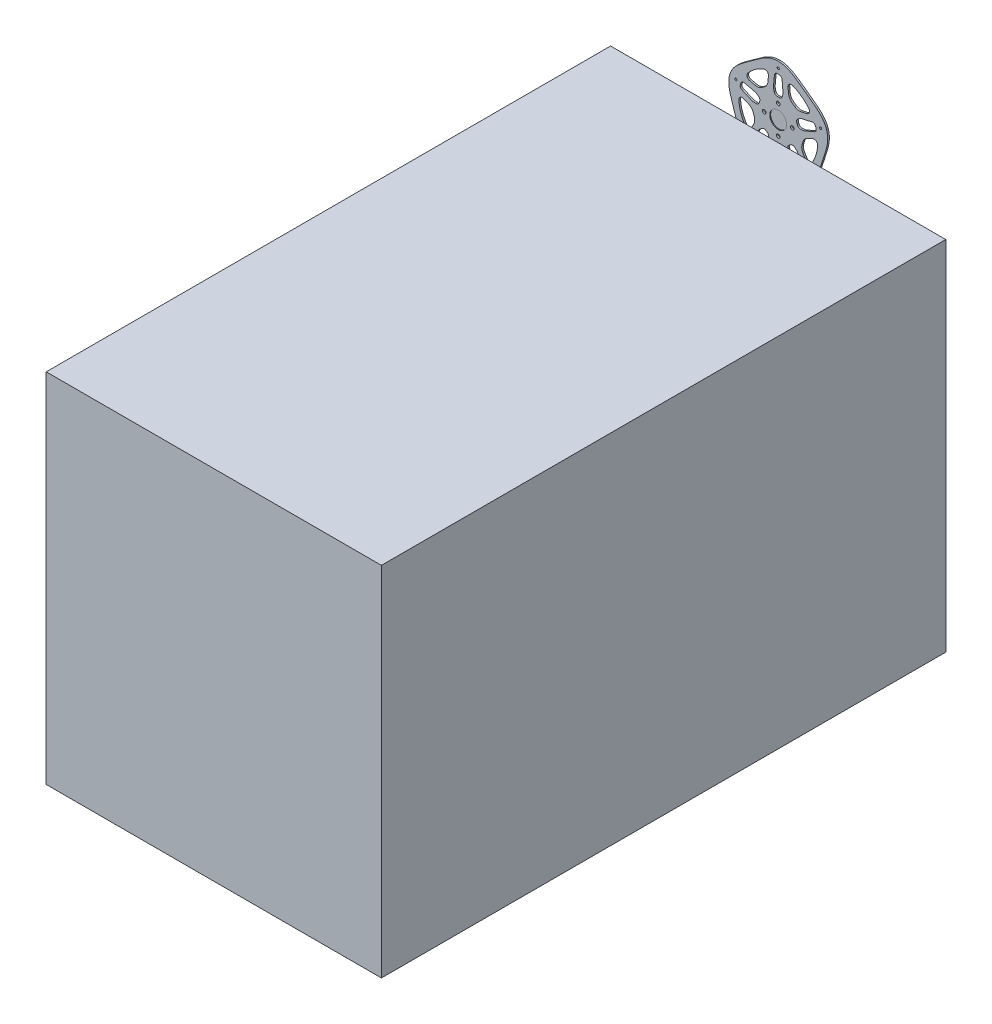
SolidWorks part; units mm, degrees
material "Stop 1060"
ref_plane "Płaszczyzna przednia" through (0, 0, 0) normal (0, 0, 1) x (1, 0, 0)
ref_plane "Płaszczyzna górna" through (0, 0, 0) normal (0, 1, 0) x (1, 0, 0)
ref_plane "Płaszczyzna prawa" through (0, 0, 0) normal (1, 0, 0) x (0, 0, -1)
sketch "Szkic1" plane through (0, 0, 0) normal (0, 0, 1) x (1, 0, 0)
  line L0 (0, 0) -> (51.1373, 70.3845) construction
  line L1 (0, 0) -> (0, 87) construction
  line L42 (64.6668, 37.9895) -> (41.3071, 32.5965)
  line L43 (69.2558, 28.7859) -> (41.6924, 22.4224)
  line L44 (38.6664, 21.1739) -> (30.949, 16.3814)
  line L45 (35.8646, 30.1162) -> (26.2605, 23.1384)
  line L46 (43.7274, 5.5975) -> (34.667, 4.9385)
  line L47 (72.9491, 17.4193) -> (46.9094, 6.3661)
  line L48 (-6.7939, 65.4105) -> (-8.4413, 46.5807)
  line L49 (-8.189, 43.317) -> (-7.2584, 39.5397)
  line L50 (69.805, 5.2211) -> (52.5779, -2.0914)
  line L51 (46.7169, -3.2838) -> (34.8456, -3.2838)
  line L52 (56.1133, -49.7624) -> (43.7657, -29.2126)
  line L53 (-7.4667, 69.6006) -> (-7.4667, 29.102) construction
  line L54 (48.7783, -56.9709) -> (34.2086, -32.7229)
  line L55 (32.0861, -30.2308) -> (25.1434, -24.3721)
  line L56 (39.725, -24.8029) -> (30.1209, -17.8251)
  line L57 (-17.3877, 59.0596) -> (-18.2365, 49.3583)
  line L58 (18.836, -39.8576) -> (15.4095, -31.4442)
  line L59 (39.1092, -63.9958) -> (20.5503, -42.6462)
  line L60 (26.5365, -64.7751) -> (14.2585, -50.6508)
  line L61 (-17.5594, 43.4157) -> (-13.891, 32.1254)
  line L62 (11.3132, -45.4452) -> (7.6448, -34.1549)
  line L63 (-29.9869, -68.7443) -> (-14.2585, -50.6508)
  line L64 (-39.1092, -63.9958) -> (-20.5503, -42.6462)
  line L65 (-18.836, -39.8576) -> (-15.4095, -31.4442)
  line L66 (-11.3132, -45.4452) -> (-7.6448, -34.1549)
  line L67 (-32.0861, -30.2308) -> (-25.1434, -24.3721)
  line L68 (-48.7783, -56.9709) -> (-34.2086, -32.7229)
  line L69 (-53.4046, -45.2543) -> (-43.7657, -29.2126)
  line L70 (-39.725, -24.8029) -> (-30.1209, -17.8251)
  line L71 (-74.6462, 7.2761) -> (-52.5779, -2.0914)
  line L72 (-72.9491, 17.4193) -> (-46.9094, 6.3661)
  line L73 (-43.7274, 5.5975) -> (-34.667, 4.9385)
  line L74 (0, 0) -> (32.9395, 101.3773) construction
  line L111 (-46.7169, -3.2838) -> (-34.8456, -3.2838)
  line L112 (-38.6664, 21.1739) -> (-30.949, 16.3814)
  line L113 (-69.2558, 28.7859) -> (-41.6924, 22.4224)
  line L114 (-59.5423, 36.8064) -> (-41.3071, 32.5965)
  line L115 (-35.8646, 30.1162) -> (-26.2605, 23.1384)
  line L116 (-29.0561, 35.0629) -> (-24.3679, 38.469)
  line L117 (24.3679, 38.469) -> (29.0561, 35.0629)
  line L118 (44.1163, -11.2877) -> (42.3256, -16.799)
  line L119 (2.8975, -45.4452) -> (-2.8975, -45.4452)
  line L120 (17.5594, 43.4157) -> (13.891, 32.1254)
  line L121 (8.189, 43.317) -> (7.2584, 39.5397)
  line L122 (16.6054, 68.0019) -> (18.2365, 49.3583)
  line L123 (5.9758, 74.7616) -> (8.4413, 46.5807)
  line L124 (-42.3256, -16.799) -> (-44.1163, -11.2877)
  circle A0 centre (0, 0) radius 79 construction
  circle A2 centre (0, 0) radius 25 construction
  circle A3 centre (0, 0) radius 3.3
  circle A4 centre (0, 25) radius 3.2
  circle A5 centre (0, 79) radius 1.9
  circle A6 centre (25, 0) radius 3.2
  circle A7 centre (0, -25) radius 3.2
  circle A8 centre (-25, 0) radius 3.2
  circle A9 centre (75.1335, 24.4123) radius 1.9
  circle A10 centre (46.435, -63.9123) radius 1.9
  circle A11 centre (-46.435, -63.9123) radius 1.9
  circle A12 centre (-75.1335, 24.4123) radius 1.9
  circle A13 centre (0, 0) radius 87 construction
  arc A54 (35.8646, 30.1162) -> (41.3071, 32.5965) centre (44.6814, 17.9809) cw
  arc A55 (38.6664, 21.1739) -> (41.6924, 22.4224) centre (43.9419, 12.6787) cw
  arc A56 (43.7274, 5.5975) -> (46.9094, 6.3661) centre (43.0021, 15.5711) ccw
  arc A57 (46.7169, -3.2838) -> (52.5779, -2.0914) centre (46.7169, 11.7162) ccw
  arc A58 (39.725, -24.8029) -> (43.7657, -29.2126) centre (30.9082, -36.9381) cw
  arc A59 (32.0861, -30.2308) -> (34.2086, -32.7229) centre (25.6369, -37.8733) cw
  circle A60 centre (0, 0) radius 70
  arc A61 (-8.189, 43.317) -> (-8.4413, 46.5807) centre (1.5207, 45.7091) cw
  arc A62 (18.836, -39.8576) -> (20.5503, -42.6462) centre (28.0974, -36.0857) ccw
  arc A63 (11.3132, -45.4452) -> (14.2585, -50.6508) centre (25.5791, -40.8099) ccw
  arc A64 (-11.3132, -45.4452) -> (-14.2585, -50.6508) centre (-25.5791, -40.8099) cw
  arc A65 (-18.2391, 49.3276) -> (-18.2365, 49.3583) centre (-3.2936, 48.051) cw
  arc A66 (-18.836, -39.8576) -> (-20.5503, -42.6462) centre (-28.0974, -36.0857) cw
  arc A67 (-32.0861, -30.2308) -> (-34.2086, -32.7229) centre (-25.6369, -37.8733) ccw
  arc A68 (-39.725, -24.8029) -> (-43.7657, -29.2126) centre (-30.9082, -36.9381) ccw
  arc A69 (8.189, 43.317) -> (8.4413, 46.5807) centre (-1.5207, 45.7091) ccw
  arc A70 (-46.7169, -3.2838) -> (-52.5779, -2.0914) centre (-46.7169, 11.7162) cw
  arc A71 (-43.7274, 5.5975) -> (-46.9094, 6.3661) centre (-43.0021, 15.5711) cw
  arc A72 (-38.6664, 21.1739) -> (-41.6924, 22.4224) centre (-43.9419, 12.6787) ccw
  arc A73 (17.5594, 43.4157) -> (18.2365, 49.3583) centre (3.2936, 48.051) ccw
  arc A74 (-41.2772, 32.5895) -> (-41.3071, 32.5965) centre (-44.6814, 17.9809) ccw
  arc A75 (-24.3679, 38.469) -> (-18.2391, 49.3276) centre (-33.1847, 50.6043) ccw
  arc A76 (-41.2772, 32.5895) -> (-29.0561, 35.0629) centre (-37.8729, 47.1981) ccw
  arc A77 (29.0561, 35.0629) -> (41.2772, 32.5895) centre (37.8729, 47.1981) ccw
  arc A78 (18.2391, 49.3276) -> (24.3679, 38.469) centre (33.1847, 50.6043) ccw
  arc A79 (42.3256, -16.799) -> (43.7498, -29.1862) centre (56.5914, -21.4342) ccw
  arc A80 (52.5496, -2.1034) -> (44.1163, -11.2877) centre (58.3822, -15.9229) ccw
  arc A81 (-2.8975, -45.4452) -> (-14.2383, -50.6276) centre (-2.8975, -60.4452) ccw
  arc A82 (14.2383, -50.6276) -> (2.8975, -45.4452) centre (2.8975, -60.4452) ccw
  arc A83 (-44.1163, -11.2877) -> (-52.5496, -2.1034) centre (-58.3822, -15.9229) ccw
  arc A84 (-43.7498, -29.1862) -> (-42.3256, -16.799) centre (-56.5914, -21.4342) ccw
  arc A85 (-7.4667, 69.6006) -> (0, 70) centre (0, 0) ccw
  arc A86 (-1.9524, 69.9728) -> (0, 70) centre (0, 0) cw
  arc A87 (-6.7939, 65.4105) -> (-1.9524, 69.9728) centre (-1.8129, 64.9747) cw
  arc A88 (-25.5554, 65.1684) -> (-59.5423, 36.8064) centre (0, 0) ccw
  arc A89 (-17.3877, 59.0596) -> (-25.5554, 65.1684) centre (-23.3649, 59.5826) ccw
  circle A90 centre (0, 0) radius 35
  arc A91 (17.3877, 59.0596) -> (25.5554, 65.1684) centre (23.3649, 59.5826) cw
  arc A92 (6.7939, 65.4105) -> (1.9524, 69.9728) centre (1.8129, 64.9747) ccw
  arc A93 (61.5421, 1.7137) -> (69.8759, -4.1664) centre (63.8865, -3.8093) cw
  arc A94 (64.3085, 13.7516) -> (67.1514, 19.766) centre (62.3548, 18.3541) ccw
  arc A95 (60.1096, 26.6743) -> (65.9447, 23.4796) centre (61.2344, 21.8025) cw
  arc A96 (50.7959, 34.7871) -> (54.0818, 44.4427) centre (49.4462, 40.6334) ccw
  arc A97 (20.6474, -58.0005) -> (17.6303, -67.7434) centre (16.1192, -61.9368) cw
  arc A98 (32.9509, -56.9116) -> (39.5495, -57.7567) centre (36.7245, -53.6313) ccw
  arc A99 (43.9437, -48.9248) -> (42.7085, -55.4616) centre (39.6579, -51.5) cw
  arc A100 (48.7813, -37.56) -> (58.9798, -37.7013) centre (53.9243, -34.4698) ccw
  arc A101 (-48.7813, -37.56) -> (-58.9798, -37.7013) centre (-53.9243, -34.4698) cw
  arc A102 (-43.9437, -48.9248) -> (-42.7085, -55.4616) centre (-39.6579, -51.5) ccw
  arc A103 (-32.9509, -56.9116) -> (-39.5495, -57.7567) centre (-36.7245, -53.6313) cw
  arc A104 (-20.6474, -58.0005) -> (-17.6303, -67.7434) centre (-16.1192, -61.9368) ccw
  arc A105 (-50.7959, 34.7871) -> (-54.0818, 44.4427) centre (-49.4462, 40.6334) cw
  arc A106 (-60.1096, 26.6743) -> (-65.9447, 23.4796) centre (-61.2344, 21.8025) ccw
  arc A107 (-64.3085, 13.7516) -> (-67.1514, 19.766) centre (-62.3548, 18.3541) cw
  arc A108 (-61.5421, 1.7137) -> (-69.8759, -4.1664) centre (-63.8865, -3.8093) ccw
  arc A109 (-7.4667, 29.102) -> (6.8673, 29.2492) centre (0, 0) ccw
  arc A110 (-1.2229, 34.9786) -> (1.2229, 34.9786) centre (0, 0) cw
  arc A111 (-7.2584, 39.5397) -> (-1.2229, 34.9786) centre (-1.4326, 40.975) ccw
  arc A112 (7.2584, 39.5397) -> (1.2229, 34.9786) centre (1.4326, 40.975) cw
  arc A113 (35.3615, 19.1216) -> (32.8887, 11.9721) centre (38.5268, 14.0244) ccw
  arc A114 (39.8474, 5.3153) -> (33.6446, 9.6459) centre (39.4122, 11.2995) cw
  arc A115 (29.113, -27.7219) -> (21.5493, -27.5795) centre (25.2435, -32.3074) ccw
  arc A116 (17.3687, -36.2546) -> (19.5705, -29.0171) centre (22.9255, -33.9915) cw
  arc A117 (-17.3687, -36.2546) -> (-19.5705, -29.0171) centre (-22.9255, -33.9915) ccw
  arc A118 (-29.113, -27.7219) -> (-21.5493, -27.5795) centre (-25.2435, -32.3074) cw
  arc A119 (-39.8474, 5.3153) -> (-33.6446, 9.6459) centre (-39.4122, 11.2995) ccw
  arc A120 (-35.3615, 19.1216) -> (-32.8887, 11.9721) centre (-38.5268, 14.0244) cw
  spline S0 degree 3 poles (0, 87) (18.2248, 86.9986) (32.2889, 73.5369) (46.435, 63.9123) knots 0 0 0 0 1 1 1 1 construction
  spline S1 degree 3 poles (82.7419, 26.8845) (77.1088, 44.2169) (59.9599, 53.4327) (46.435, 63.9123) knots 0 0 0 0 1 1 1 1 construction
  spline S2 degree 3 poles (82.7419, 26.8845) (88.3724, 9.5512) (79.9156, -7.9844) (75.1335, -24.4123) knots 0 0 0 0 1 1 1 1 construction
  spline S3 degree 3 poles (51.1373, -70.3845) (65.8807, -59.6711) (69.3462, -40.5137) (75.1335, -24.4123) knots 0 0 0 0 1 1 1 1 construction
  spline S4 degree 3 poles (51.1373, -70.3845) (36.3923, -81.0957) (17.1016, -78.4715) (0, -79) knots 0 0 0 0 1 1 1 1 construction
  spline S5 degree 3 poles (-51.1373, -70.3845) (-36.3923, -81.0957) (-17.1016, -78.4715) (0, -79) knots 0 0 0 0 1 1 1 1 construction
  spline S6 degree 3 poles (-51.1373, -70.3845) (-65.8807, -59.6711) (-69.3462, -40.5137) (-75.1335, -24.4123) knots 0 0 0 0 1 1 1 1 construction
  spline S7 degree 3 poles (-82.7419, 26.8845) (-88.3724, 9.5512) (-79.9156, -7.9844) (-75.1335, -24.4123) knots 0 0 0 0 1 1 1 1 construction
  spline S8 degree 3 poles (-82.7419, 26.8845) (-77.1088, 44.2169) (-59.9599, 53.4327) (-46.435, 63.9123) knots 0 0 0 0 1 1 1 1 construction
  spline S9 degree 3 poles (0, 87) (-18.2248, 86.9986) (-32.2889, 73.5369) (-46.435, 63.9123) knots 0 0 0 0 1 1 1 1 construction
  spline S10 degree 1 poles (0, 90) (48.1992, 66.3406) knots 0 0 1 1 construction
  spline S11 degree 1 poles (85.5951, 27.8115) (48.1992, 66.3406) knots 0 0 1 1 construction
  spline S12 degree 1 poles (85.5951, 27.8115) (77.988, -25.3398) knots 0 0 1 1 construction
  spline S13 degree 1 poles (52.9007, -72.8115) (77.988, -25.3398) knots 0 0 1 1 construction
  spline S14 degree 1 poles (52.9007, -72.8115) (0, -82.0014) knots 0 0 1 1 construction
  spline S15 degree 1 poles (-52.9007, -72.8115) (0, -82.0014) knots 0 0 1 1 construction
  spline S16 degree 1 poles (-52.9007, -72.8115) (-77.988, -25.3398) knots 0 0 1 1 construction
  spline S17 degree 1 poles (-85.5951, 27.8115) (-77.988, -25.3398) knots 0 0 1 1 construction
  spline S18 degree 1 poles (-85.5951, 27.8115) (-48.1992, 66.3406) knots 0 0 1 1 construction
  spline S19 degree 1 poles (0, 90) (-48.1992, 66.3406) knots 0 0 1 1 construction
  spline S20 degree 3 poles (0, 90) (1.2173, 89.9999) (3.6733, 89.8856) (8.3842, 89.2383) (14.0239, 87.7208) (20.3782, 85.0183) (26.3875, 81.6762) (32.115, 77.9195) (37.6265, 73.9608) (42.0815, 70.6707) (45.5966, 68.1385) (47.3232, 66.9366) (48.1992, 66.3406) knots -0.000004 -0.000004 -0.000004 -0.000004 0.062609 0.125222 0.250448 0.375675 0.500901 0.626127 0.751353 0.87658 0.939193 1.001806 1.001806 1.001806 1.001806
  spline S21 degree 3 poles (48.1992, 66.3406) (49.0368, 65.6916) (50.7135, 64.4209) (54.2079, 61.8604) (58.7136, 58.6401) (64.1818, 54.6216) (69.5245, 50.3354) (74.56, 45.6529) (79.0938, 40.4447) (82.2798, 35.55) (84.3511, 31.2697) (85.2188, 28.9693) (85.5951, 27.8115) knots -0.000004 -0.000004 -0.000004 -0.000004 0.062609 0.125222 0.250448 0.375675 0.500901 0.626127 0.751353 0.87658 0.939193 1.001806 1.001806 1.001806 1.001806
  spline S22 degree 3 poles (85.5951, 27.8115) (85.9712, 26.6537) (86.6214, 24.2826) (87.4616, 19.6023) (87.761, 13.7697) (87.1544, 6.8913) (85.8329, 0.1433) (84.03, -6.4647) (81.9681, -12.9298) (80.2157, -18.1835) (78.8937, -22.3089) (78.2841, -24.3225) (77.988, -25.3398) knots -0.000004 -0.000004 -0.000004 -0.000004 0.062609 0.125222 0.250448 0.375675 0.500901 0.626127 0.751353 0.87658 0.939193 1.001806 1.001806 1.001806 1.001806
  spline S23 degree 3 poles (77.988, -25.3398) (77.6296, -26.337) (76.9392, -28.3242) (75.5838, -32.4389) (73.9136, -37.7192) (71.7815, -44.1615) (69.356, -50.5673) (66.4588, -56.8033) (62.9065, -62.7246) (59.236, -67.2672) (55.8052, -70.5598) (53.8855, -72.0959) (52.9007, -72.8115) knots -0.000004 -0.000004 -0.000004 -0.000004 0.062609 0.125222 0.250448 0.375675 0.500901 0.626127 0.751353 0.87658 0.939193 1.001806 1.001806 1.001806 1.001806
  spline S24 degree 3 poles (52.9007, -72.8115) (51.9158, -73.527) (49.8616, -74.8781) (45.67, -77.1235) (40.2154, -79.2106) (33.4862, -80.7592) (26.6601, -81.5876) (19.8184, -81.9149) (13.0325, -81.9518) (7.4945, -81.9087) (3.1624, -81.9262) (1.0591, -81.9687) (0, -82.0014) knots -0.000004 -0.000004 -0.000004 -0.000004 0.062609 0.125222 0.250448 0.375675 0.500901 0.626127 0.751353 0.87658 0.939193 1.001806 1.001806 1.001806 1.001806
  spline S25 degree 3 poles (0, -82.0014) (-1.0591, -81.9687) (-3.1624, -81.9262) (-7.4945, -81.9087) (-13.0325, -81.9518) (-19.8184, -81.9149) (-26.6601, -81.5876) (-33.4862, -80.7592) (-40.2154, -79.2106) (-45.67, -77.1235) (-49.8616, -74.8781) (-51.9158, -73.527) (-52.9007, -72.8115) knots -0.000004 -0.000004 -0.000004 -0.000004 0.062609 0.125222 0.250448 0.375675 0.500901 0.626127 0.751353 0.87658 0.939193 1.001806 1.001806 1.001806 1.001806
  spline S26 degree 3 poles (-52.9007, -72.8115) (-53.8855, -72.0959) (-55.8052, -70.5598) (-59.236, -67.2672) (-62.9065, -62.7246) (-66.4588, -56.8033) (-69.356, -50.5673) (-71.7815, -44.1615) (-73.9136, -37.7192) (-75.5838, -32.4389) (-76.9392, -28.3242) (-77.6296, -26.337) (-77.988, -25.3398) knots -0.000004 -0.000004 -0.000004 -0.000004 0.062609 0.125222 0.250448 0.375675 0.500901 0.626127 0.751353 0.87658 0.939193 1.001806 1.001806 1.001806 1.001806
  spline S27 degree 3 poles (-77.988, -25.3398) (-78.2841, -24.3225) (-78.8937, -22.3089) (-80.2157, -18.1835) (-81.9681, -12.9298) (-84.03, -6.4647) (-85.8329, 0.1433) (-87.1544, 6.8913) (-87.761, 13.7697) (-87.4616, 19.6023) (-86.6214, 24.2826) (-85.9712, 26.6537) (-85.5951, 27.8115) knots -0.000004 -0.000004 -0.000004 -0.000004 0.062609 0.125222 0.250448 0.375675 0.500901 0.626127 0.751353 0.87658 0.939193 1.001806 1.001806 1.001806 1.001806
  spline S28 degree 3 poles (-85.5951, 27.8115) (-85.2188, 28.9693) (-84.3511, 31.2697) (-82.2798, 35.55) (-79.0938, 40.4447) (-74.56, 45.6529) (-69.5245, 50.3354) (-64.1818, 54.6216) (-58.7136, 58.6401) (-54.2079, 61.8604) (-50.7135, 64.4209) (-49.0368, 65.6916) (-48.1992, 66.3406) knots -0.000004 -0.000004 -0.000004 -0.000004 0.062609 0.125222 0.250448 0.375675 0.500901 0.626127 0.751353 0.87658 0.939193 1.001806 1.001806 1.001806 1.001806
  spline S29 degree 3 poles (-48.1992, 66.3406) (-47.3232, 66.9366) (-45.5966, 68.1385) (-42.0815, 70.6707) (-37.6265, 73.9608) (-32.115, 77.9195) (-26.3875, 81.6762) (-20.3782, 85.0183) (-14.0239, 87.7208) (-8.3842, 89.2383) (-3.6733, 89.8856) (-1.2173, 89.9999) (0, 90) knots -0.000004 -0.000004 -0.000004 -0.000004 0.062609 0.125222 0.250448 0.375675 0.500901 0.626127 0.751353 0.87658 0.939193 1.001806 1.001806 1.001806 1.001806
  point P18 (0, 0)
  point P27 (0, 0)
  point P64 (0, 0)
  point P72 (-8.5859, 44.9279)
  point P166 (0, 0)
  point P188 (0.227, 0)
  point P198 (0, 0)
  point P260 (0, 0)
  point P291 (0, 0)
  point P369 (0.5409, 0.0601)
  dimension "D1" = 158
  dimension "D2" = 6.6
  dimension "D3" = 50
  dimension "D4" = 3.8
  dimension "D5" = 6.4
  dimension "D8" = 174
  dimension "D13" = 5
  dimension "D14" = 6
  dimension "D15" = 10
  dimension "D10" = 70
  dimension "D11" = 140
  dimension "D16" = 10
  dimension "D18" = 15
  dimension "D23" = 15
  dimension "D26" = 6
  dimension "D27" = 6
  dimension "D29" = 70
  dimension "D9" = 36
  dimension "D12" = 5
  dimension "D17" = 18
  dimension "D20" = 5
  dimension "D21" = 11.8713
  dimension "D22" = 18
  dimension "D19" = 3
  dimension "D6" = 4
  dimension "D7" = 5
  dimension "D24" = 5
  dimension "D25" = 5
  dimension "D28" = 5
extrude "Dodanie-wyciągnięcie1" add sketch "Szkic1" along normal blind 3
sketch "Szkic2" plane through (0, 0, 3) normal (0, 0, 1) x (1, 0, 0)
  circle A0 centre (0, 0) radius 15
  dimension "D1" = 30
extrude "Wytnij-wyciągnięcie1" cut sketch "Szkic2" against normal blind 1.5
ref_plane "Płaszczyzna1" through (0, 0, 3.1) normal (0, 0, 1) x (1, 0, 0)
sketch "Szkic3" plane through (0, 0, 3.1) normal (0, 0, 1) x (1, 0, 0)
  line L1 (-296.9479, -668.4565) -> (296.9479, -668.4565)
  line L2 (-296.9479, -668.4565) -> (-296.9479, -35.2062)
  line L3 (-296.9479, -35.2062) -> (296.9479, -35.2062)
  line L4 (296.9479, -668.4565) -> (296.9479, -35.2062)
  line L5 (0, -35.2062) -> (0, -668.4565) construction
  line L6 (-296.9479, -351.8314) -> (296.9479, -351.8314) construction
  point P0 (0, -351.8314)
extrude "Dodanie-wyciągnięcie2" add sketch "Szkic3" along normal blind 1000 separate body
sketch "Sketch1" plane through (0, 0, 0) normal (0, 0, -1) x (-1, 0, 0)
  line L0 (0, 0) -> (-16.4631, 16.4631) construction
  line L1 (0, 0) -> (14.4362, 0) construction
  circle A0 centre (0, 0) radius 25 construction
  circle A1 centre (-17.6777, 17.6777) radius 2.15
  circle A2 centre (17.6777, 17.6777) radius 2.15
  circle A3 centre (17.6777, -17.6777) radius 2.15
  circle A4 centre (-17.6777, -17.6777) radius 2.15
  point P17 (0, 0)
  dimension "D1" = 135
  dimension "D2" = 4.3
  dimension "D3" = 4
extrude "Cut-Extrude1" [suppressed] cut sketch "Sketch1" against normal blind 7
sketch "Sketch2" plane through (0, 0, 3) normal (0, 0, 1) x (1, 0, 0)
  line L1 (-5.15, 2.9734) -> (-5.15, -2.9734)
  line L2 (-5.15, -2.9734) -> (0, -5.9467)
  line L3 (0, -5.9467) -> (5.15, -2.9734)
  line L4 (5.15, -2.9734) -> (5.15, 2.9734)
  line L5 (5.15, 2.9734) -> (0, 5.9467)
  line L6 (0, 5.9467) -> (-5.15, 2.9734)
  circle A0 centre (0, 0) radius 5.15 construction
  dimension "D1" = 10.3
extrude "Cut-Extrude2" [suppressed] cut sketch "Sketch2" against normal blind 5.5
